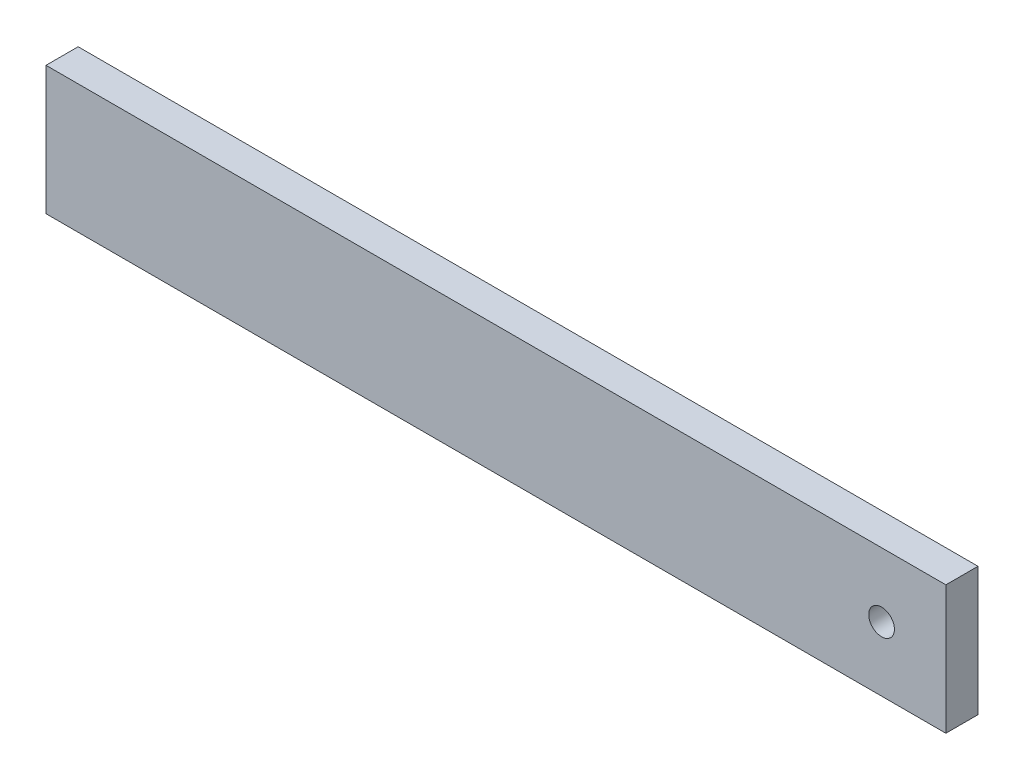
SolidWorks part; units mm, degrees
ref_plane "Plan de face" through (0, 0, 0) normal (0, 0, 1) x (1, 0, 0)
ref_plane "Plan de dessus" through (0, 0, 0) normal (0, 1, 0) x (1, 0, 0)
ref_plane "Plan de droite" through (0, 0, 0) normal (1, 0, 0) x (0, 0, -1)
sketch "Esquisse1" plane through (0, 0, 0) normal (0, 0, 1) x (1, 0, 0)
  line L0 (0, 10) -> (-140, 10) construction
  line L1 (0, 0) -> (-140, 0)
  line L2 (0, 0) -> (0, 20)
  line L3 (0, 20) -> (-140, 20)
  line L4 (-140, 0) -> (-140, 20)
  circle A0 centre (-10, 10) radius 2
  dimension "D5" = 10
  dimension "D1" = 20
  dimension "D2" = 140
extrude "Boss.-Extru.1" add sketch "Esquisse1" along normal blind 5
